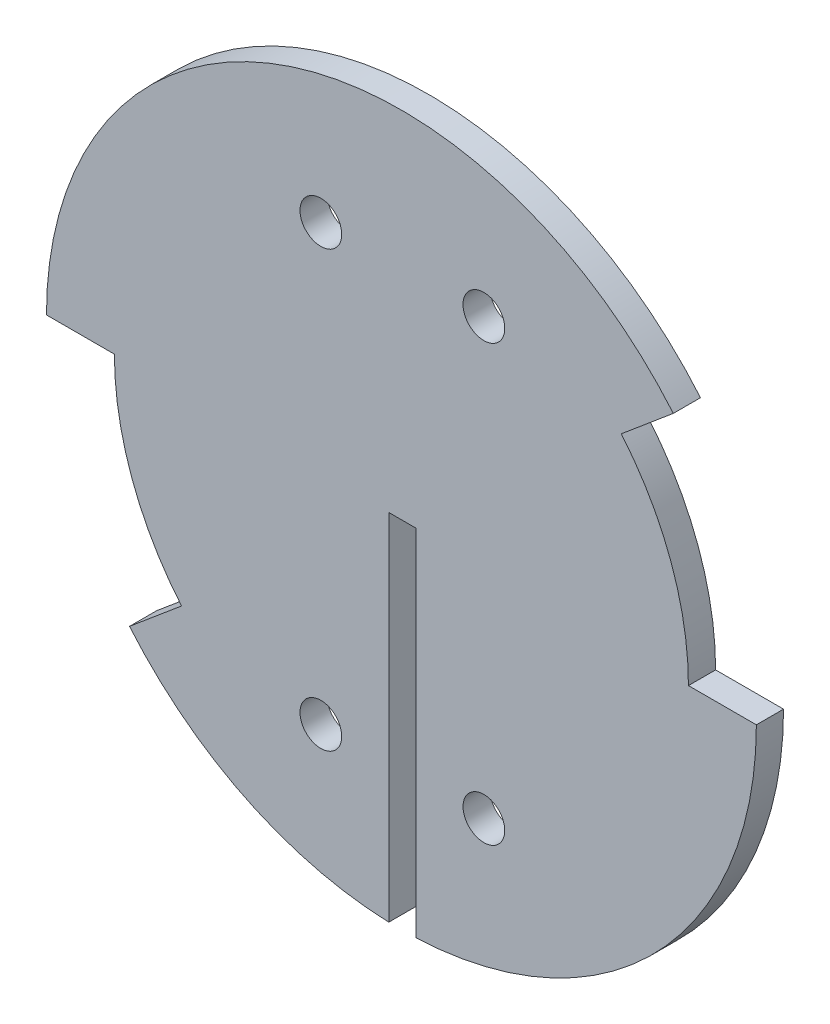
SolidWorks part; units mm, degrees
ref_plane "Front Plane" through (0, 0, 0) normal (0, 0, 1) x (1, 0, 0)
ref_plane "Top Plane" through (0, 0, 0) normal (0, 1, 0) x (1, 0, 0)
ref_plane "Right Plane" through (0, 0, 0) normal (1, 0, 0) x (0, 0, -1)
sketch "Sketch1" plane through (0, 0, 0) normal (0, 0, 1) x (1, 0, 0)
  circle A0 centre (0, 0) radius 66.3575
extrude "Boss-Extrude1" add sketch "Sketch1" along normal blind 5.08
sketch "Sketch3" plane through (0, 0, 0) normal (0, 0, 1) x (1, 0, 0)
  line L0 (0, 0) -> (66.3575, 0) construction
  line L1 (2.7181, -67.8586) -> (-2.3619, -67.8586)
  line L2 (2.7181, -67.8586) -> (2.7181, 0.0229)
  line L3 (2.7181, 0.0229) -> (-2.3619, 0.0229)
  line L4 (-2.3619, -67.8586) -> (-2.3619, 0.0229)
  line L5 (2.7181, -67.8586) -> (-2.3619, 0.0229) construction
  line L6 (2.7181, 0.0229) -> (-2.3619, -67.8586) construction
  line L7 (66.3575, 0) -> (-66.3575, 0) construction
  line L8 (-53.6575, 0) -> (-66.3575, 0)
  line L9 (-41.104, -34.4904) -> (-50.8328, -42.6538)
  line L10 (41.104, 34.4904) -> (50.8328, 42.6538)
  line L11 (53.6575, 0) -> (66.3575, 0)
  circle A0 centre (0, 0) radius 19.05
  circle A2 centre (-15.0619, -40.64) radius 3.9006
  circle A3 centre (15.4181, -40.64) radius 3.9006
  circle A4 centre (0, 0) radius 66.3575 construction
  circle A5 centre (15.4181, 40.64) radius 3.9006
  circle A6 centre (-15.0619, 40.64) radius 3.9006
  arc A8 (-41.104, -34.4904) -> (-53.6575, 0) centre (0, 0) cw
  circle A9 centre (0, 0) radius 53.6575
  circle A10 centre (0, 0) radius 53.6575 construction
  arc A11 (41.104, 34.4904) -> (53.6575, 0) centre (0, 0) cw
  arc A12 (-66.3575, 0) -> (-50.7671, -42.732) centre (0, 0) ccw
  arc A13 (50.8328, 42.6538) -> (66.3575, 0) centre (0, 0) cw
  point P3 (0.1781, -33.9179)
  point P31 (0, 0)
  dimension "D1" = 5.08
  dimension "D4" = 40.64
  dimension "D2" = 12.7
  dimension "D3" = 12.7
  dimension "D5" = 40.64
  dimension "D8" = 67.8815
  dimension "D7" = 2
  dimension "D6" = 12.7
extrude "Cut-Extrude2" cut sketch "Sketch3" along normal up to next contours L8 A12 L9 A8 | A13 L10 A11 L11 | A3 | A2 | A5 | A6 | L2 L3 L4 L1
